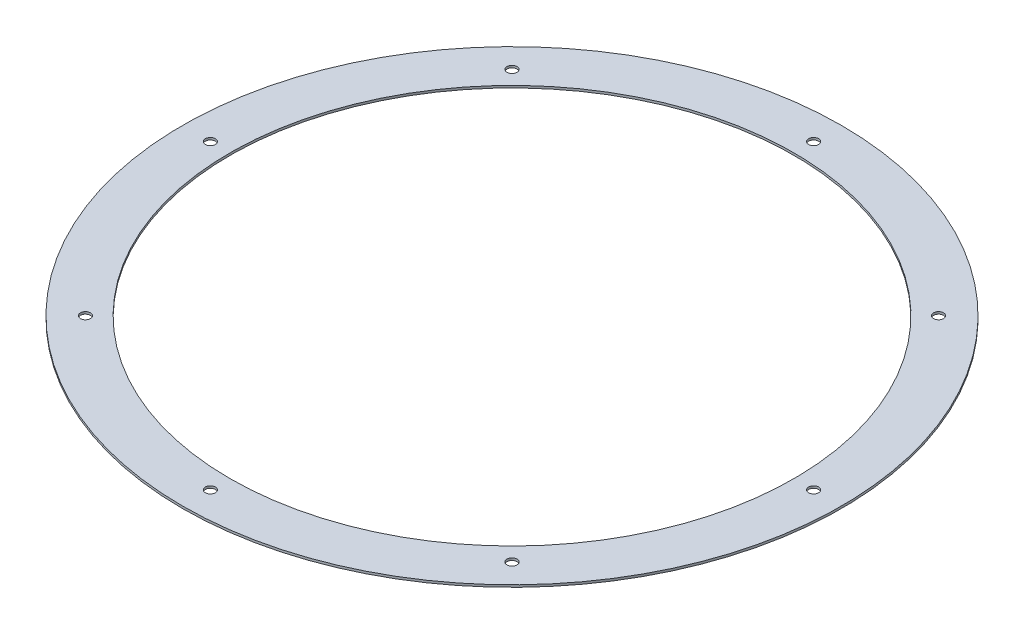
SolidWorks part; units mm, degrees
material "ASTM A36 Steel"
ref_plane "Front Plane" through (0, 0, 0) normal (0, 0, 1) x (1, 0, 0)
ref_plane "Top Plane" through (0, 0, 0) normal (0, 1, 0) x (1, 0, 0)
ref_plane "Right Plane" through (0, 0, 0) normal (1, 0, 0) x (0, 0, -1)
sketch "Sketch1" plane through (0, 0, 0) normal (0, 1, 0) x (1, 0, 0)
  circle A0 centre (0, 0) radius 252.5
  circle A1 centre (0, 0) radius 295
  dimension "D1" = 505
  dimension "D2" = 590
extrude "Boss-Extrude1" add sketch "Sketch1" along normal blind 2
sketch "Sketch2" plane through (0, 2, 0) normal (0, 1, 0) x (1, 0, 0)
  circle A0 centre (0, 0) radius 270 construction
  circle A1 centre (0, 270) radius 4.5
  dimension "D1" = 9
  dimension "D2" = 540
extrude "Cut-Extrude1" cut sketch "Sketch2" against normal blind 2
pattern_circular "CirPattern1" count 8 every 45 about axis through (0, 0, 0) along (0, 1, 0) of "Cut-Extrude1"
